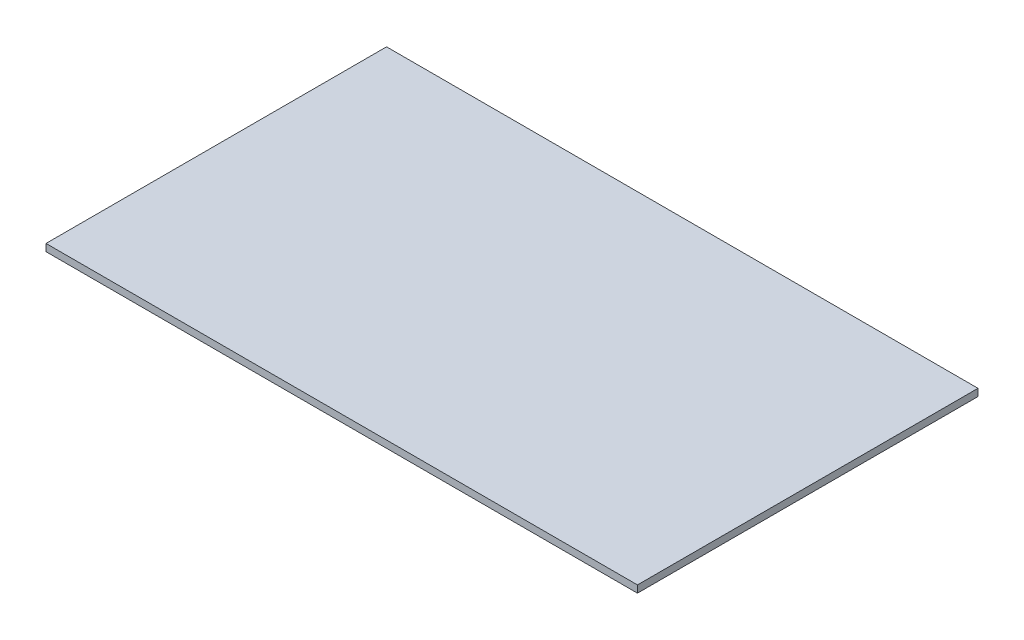
SolidWorks part; units mm, degrees
ref_plane "Front Plane" through (0, 0, 0) normal (0, 0, 1) x (1, 0, 0)
ref_plane "Top Plane" through (0, 0, 0) normal (0, 1, 0) x (1, 0, 0)
ref_plane "Right Plane" through (0, 0, 0) normal (1, 0, 0) x (0, 0, -1)
sketch "Sketch1" plane through (0, 0, 0) normal (0, 1, 0) x (1, 0, 0)
  line L1 (0, 0) -> (82.5, 0)
  line L2 (0, 0) -> (0, -47.5)
  line L3 (0, -47.5) -> (82.5, -47.5)
  line L4 (82.5, 0) -> (82.5, -47.5)
extrude "Boss-Extrude1" add sketch "Sketch1" along normal blind 1 contours L1 L4 L3 L2
